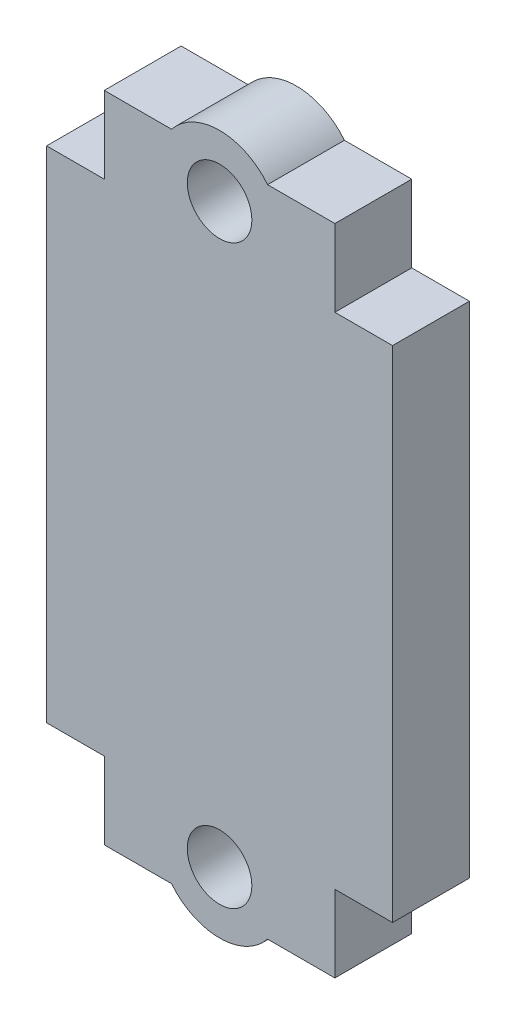
SolidWorks part; units mm, degrees
ref_plane "Front Plane" through (0, 0, 0) normal (0, 0, 1) x (1, 0, 0)
ref_plane "Top Plane" through (0, 0, 0) normal (0, 1, 0) x (1, 0, 0)
ref_plane "Right Plane" through (0, 0, 0) normal (1, 0, 0) x (0, 0, -1)
sketch "Sketch1" plane through (0, 0, 0) normal (0, 0, 1) x (1, 0, 0)
  line L0 (0, 16.25) -> (14.0956, 16.25) construction
  line L1 (0, 0) -> (-22.5, 0)
  line L2 (0, 0) -> (0, 32.5)
  line L3 (0, 32.5) -> (-22.5, 32.5)
  line L4 (-22.5, 0) -> (-22.5, 32.5)
  line L5 (-18.75, 32.5) -> (-3.75, 32.5)
  line L6 (-18.75, 32.5) -> (-18.75, 37.5)
  line L7 (-18.75, 37.5) -> (-3.75, 37.5)
  line L8 (-3.75, 32.5) -> (-3.75, 37.5)
  line L9 (-3.75, 0) -> (-3.75, -5)
  line L10 (-18.75, -5) -> (-3.75, -5)
  line L11 (-18.75, 0) -> (-18.75, -5)
  line L12 (-18.75, 0) -> (-3.75, 0)
  line L13 (-14.3725, 37.5) -> (-8.1275, 37.5)
  line L14 (-14.3725, -5) -> (-8.1275, -5)
  circle A0 centre (-11.25, 35) radius 2.1
  circle A1 centre (-11.25, -2.5) radius 2.1
  arc A2 (-8.1275, 37.5) -> (-14.3725, 37.5) centre (-11.25, 35) ccw
  arc A3 (-8.1275, -5) -> (-14.3725, -5) centre (-11.25, -2.5) cw
  point P9 (-11.25, 32.5)
  point P10 (-11.25, 37.5)
  dimension "D5" = 4.2
  dimension "D6" = 2.5
  dimension "D7" = 7.5
  dimension "D8" = 4.2
  dimension "D9" = 4
  dimension "D1" = 22.5
  dimension "D2" = 32.5
  dimension "D3" = 5
  dimension "D4" = 15
extrude "Boss-Extrude1" add sketch "Sketch1" along normal blind 5 contours L3 L8 L7 L6 A0 | L4 L1 L2 L3 | L1 L11 L10 L9 A1 | A3 L10 | A2 L13
